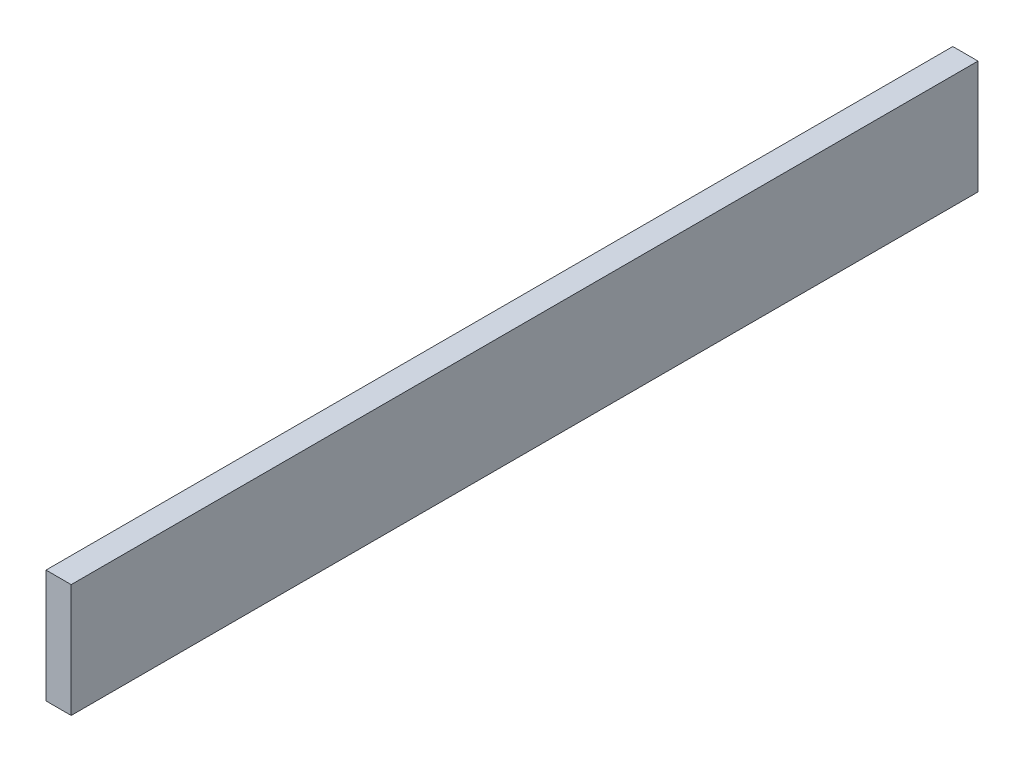
SolidWorks part; units mm, degrees
ref_plane "Plan de face" through (0, 0, 0) normal (0, 0, 1) x (1, 0, 0)
ref_plane "Plan de dessus" through (0, 0, 0) normal (0, 1, 0) x (1, 0, 0)
ref_plane "Plan de droite" through (0, 0, 0) normal (1, 0, 0) x (0, 0, -1)
sketch "Esquisse1" plane through (0, 0, 0) normal (1, 0, 0) x (0, 0, -1)
  line L1 (592.1074, 28.7695) -> (-127.8926, 28.7695)
  line L2 (592.1074, 28.7695) -> (592.1074, -61.2305)
  line L3 (592.1074, -61.2305) -> (-127.8926, -61.2305)
  line L4 (-127.8926, 28.7695) -> (-127.8926, -61.2305)
  dimension "D1" = 720
  dimension "D2" = 90
extrude "Boss.-Extru.1" add sketch "Esquisse1" along normal blind 20
